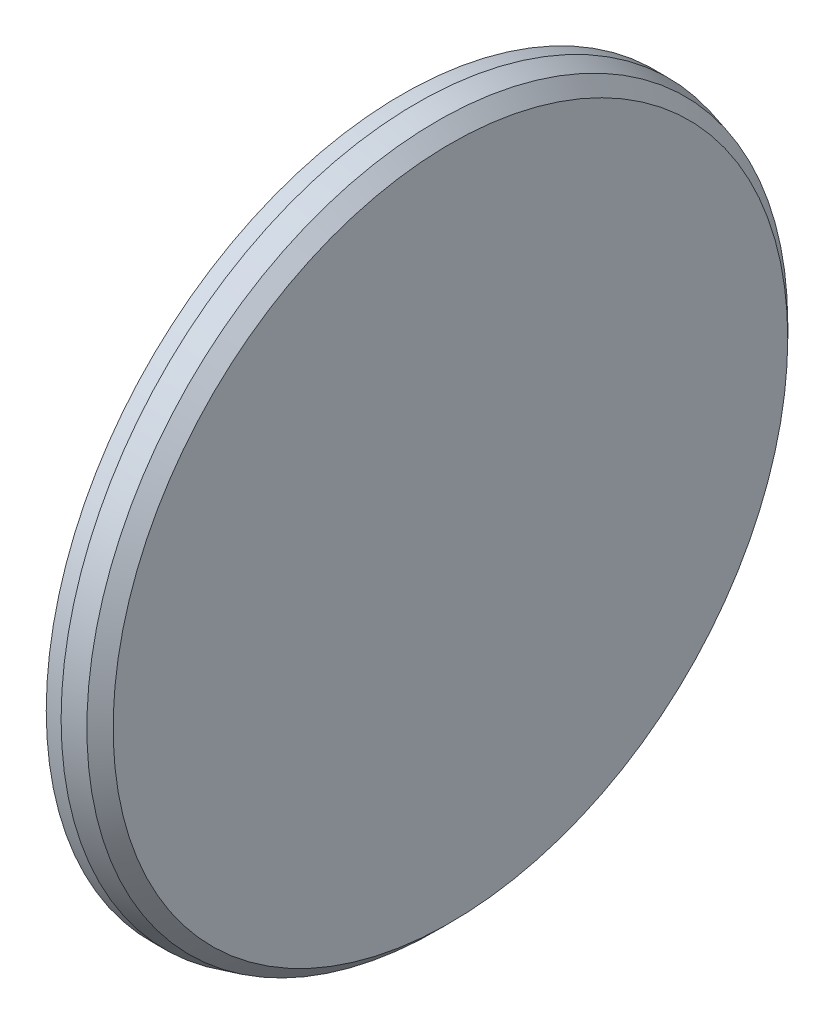
SolidWorks part; units mm, degrees
material "1060 Alloy"
ref_plane "Front Plane" through (0, 0, 0) normal (0, 0, 1) x (1, 0, 0)
ref_plane "Top Plane" through (0, 0, 0) normal (0, 1, 0) x (1, 0, 0)
ref_plane "Right Plane" through (0, 0, 0) normal (1, 0, 0) x (0, 0, -1)
sketch "Sketch1" plane through (0, 0, 0) normal (0, 1, 0) x (1, 0, 0)
  line L0 (0, 0) -> (-85, 0) construction
  line L1 (-85, 0) -> (-85, 100)
  line L2 (-85, 100) -> (-30, 100)
  line L3 (-30, 100) -> (-30, 433.75)
  line L4 (-30, 433.75) -> (-65, 433.75)
  line L5 (-65, 433.75) -> (-65, 478.75)
  line L6 (-65, 478.75) -> (-45, 478.75)
  line L7 (-45, 478.75) -> (-17.6795, 471.4295)
  line L8 (-17.6795, 471.4295) -> (0, 453.75)
  line L9 (0, 453.75) -> (0, 0)
  line L10 (0, 0) -> (-85, 0)
  point P10 (-55, 478.75)
  dimension "D1" = 100
  dimension "D2" = 20
  dimension "D3" = 45
  dimension "D4" = 15
  dimension "D5" = 45
  dimension "D6" = 30
  dimension "D7" = 65
  dimension "D8" = 85
  dimension "D9" = 478.75
  dimension "D10" = 453.75
revolve "Revolve1" add sketch "Sketch1" angle 360 about L0
sketch "Sketch2" plane through (-30, 0, 0) normal (-1, 0, 0) x (0, 0, 1)
  line L0 (0, 100) -> (0, 433.75) construction
  line L1 (20, 105.8301) -> (20, 422.6867)
  line L2 (-20, 105.8301) -> (-20, 365.0877)
  line L3 (-20, 100) -> (-20, 433.75) construction
  line L4 (20, 100) -> (20, 433.75) construction
  line L5 (83.3471, 68.2148) -> (287.0187, 310.9411)
  line L6 (52.7054, 93.9263) -> (219.353, 292.5292)
  line L7 (64.2788, 76.6044) -> (278.8091, 332.2718) construction
  line L8 (107.6952, -1.319) -> (419.7381, 53.7026)
  line L9 (100.7493, 38.0734) -> (356.0683, 83.093)
  line L10 (98.4808, 17.3648) -> (427.1604, 75.3199) construction
  line L11 (81.6515, -70.2355) -> (356.0574, -228.6639)
  line L12 (101.6515, -35.5945) -> (326.1753, -165.2234)
  line L13 (86.6025, -50) -> (375.6385, -216.875) construction
  line L14 (17.4022, -106.2881) -> (125.7735, -404.036)
  line L15 (54.9899, -92.6073) -> (143.6612, -336.2299)
  line L16 (34.202, -93.9693) -> (148.3512, -407.5917) construction
  line L17 (-54.9899, -92.6073) -> (-163.3612, -390.3552)
  line L18 (-17.4022, -106.2881) -> (-106.0735, -349.9107)
  line L19 (-34.202, -93.9693) -> (-148.3512, -407.5917) construction
  line L20 (-101.6515, -35.5945) -> (-376.0574, -194.0229)
  line L21 (-81.6515, -70.2355) -> (-306.1753, -199.8644)
  line L22 (-86.6025, -50) -> (-375.6385, -216.875) construction
  line L23 (-100.7493, 38.0734) -> (-412.7922, 93.0949)
  line L24 (-107.6952, -1.319) -> (-363.0142, 43.7007)
  line L25 (-98.4808, 17.3648) -> (-427.1604, 75.3199) construction
  line L26 (-52.7054, 93.9263) -> (-256.3769, 336.6526)
  line L27 (-83.3471, 68.2148) -> (-249.9948, 266.8177)
  line L28 (-64.2788, 76.6044) -> (-278.8091, 332.2718) construction
  circle A0 centre (0, 0) radius 100 construction
  circle A1 centre (0, 0) radius 433.75 construction
  arc A4 (20, 422.6867) -> (30.708, 432.6616) centre (30, 422.6867) cw
  arc A5 (287.0187, 310.9411) -> (301.6332, 311.6993) centre (294.6791, 304.5132) cw
  arc A6 (-20, 365.0877) -> (-92.8428, 423.6972) centre (-80, 365.0877) ccw
  arc A7 (20, 105.8301) -> (27.2727, 96.2091) centre (30, 105.8301) ccw
  arc A8 (-20, 105.8301) -> (-27.2727, 96.2091) centre (-30, 105.8301) cw
  arc A9 (219.353, 292.5292) -> (201.2256, 384.2491) centre (173.3903, 331.0964) ccw
  arc A10 (83.3471, 68.2148) -> (82.7342, 56.1699) centre (91.0076, 61.7869) ccw
  arc A11 (52.7054, 93.9263) -> (40.9499, 91.231) centre (45.0449, 100.3542) cw
  arc A12 (419.7381, 53.7026) -> (431.4209, 44.8895) centre (421.4746, 43.8545) cw
  arc A13 (356.0683, 83.093) -> (401.1383, 165.0066) centre (345.6494, 142.1814) ccw
  arc A14 (107.6952, -1.319) -> (99.4834, -10.1519) centre (109.4317, -11.167) ccw
  arc A15 (100.7493, 38.0734) -> (90.0116, 43.5649) centre (99.0128, 47.9214) cw
  arc A16 (356.0574, -228.6639) -> (359.342, -242.9247) centre (351.0574, -237.3241) cw
  arc A17 (326.1753, -165.2234) -> (413.3539, -131.4443) centre (356.1753, -113.2618) ccw
  arc A18 (81.6515, -70.2355) -> (69.6832, -71.7234) centre (76.6515, -78.8958) ccw
  arc A19 (101.6515, -35.5945) -> (96.9559, -24.4857) centre (106.6515, -26.9343) cw
  arc A20 (125.7735, -404.036) -> (119.1229, -417.0717) centre (116.3766, -407.4562) cw
  arc A21 (143.6612, -336.2299) -> (232.1567, -366.391) centre (200.0428, -315.7086) ccw
  arc A22 (17.4022, -106.2881) -> (7.2775, -99.7348) centre (8.0052, -109.7083) ccw
  arc A23 (54.9899, -92.6073) -> (58.5334, -81.0792) centre (64.3868, -89.1871) cw
  arc A24 (-163.3612, -390.3552) -> (-176.835, -396.0662) centre (-172.7582, -386.935) cw
  arc A25 (-106.0735, -349.9107) -> (-57.6693, -429.8992) centre (-49.692, -370.4319) ccw
  arc A26 (-54.9899, -92.6073) -> (-58.5334, -81.0792) centre (-64.3868, -89.1871) ccw
  arc A27 (-17.4022, -106.2881) -> (-7.2775, -99.7348) centre (-8.0052, -109.7083) cw
  arc A28 (-376.0574, -194.0229) -> (-390.0499, -189.7369) centre (-381.0574, -185.3626) cw
  arc A29 (-306.1753, -199.8644) -> (-320.5111, -292.2528) centre (-276.1753, -251.8259) ccw
  arc A30 (-101.6515, -35.5945) -> (-96.9559, -24.4857) centre (-106.6515, -26.9343) ccw
  arc A31 (-81.6515, -70.2355) -> (-69.6832, -71.7234) centre (-76.6515, -78.8958) cw
  arc A32 (-412.7922, 93.0949) -> (-420.7561, 105.3723) centre (-411.0557, 102.943) cw
  arc A33 (-363.0142, 43.7007) -> (-433.3822, -17.8581) centre (-373.4331, -15.3878) ccw
  arc A34 (-100.7493, 38.0734) -> (-90.0116, 43.5649) centre (-99.0128, 47.9214) ccw
  arc A35 (-107.6952, -1.319) -> (-99.4834, -10.1519) centre (-109.4317, -11.167) cw
  arc A36 (-256.3769, 336.6526) -> (-254.5859, 351.1767) centre (-248.7165, 343.0804) cw
  arc A37 (-249.9948, 266.8177) -> (-343.469, 264.8926) centre (-295.9574, 228.2504) ccw
  arc A38 (-52.7054, 93.9263) -> (-40.9499, 91.231) centre (-45.0449, 100.3542) ccw
  arc A39 (-83.3471, 68.2148) -> (-82.7342, 56.1699) centre (-91.0076, 61.7869) cw
  arc A40 (82.7342, 56.1699) -> (40.9499, 91.231) centre (0, 0) ccw
  arc A41 (-420.7561, 105.3723) -> (-433.3822, -17.8581) centre (0, 0) ccw
  arc A42 (-254.5859, 351.1767) -> (-343.469, 264.8926) centre (0, 0) ccw
  arc A43 (30.708, 432.6616) -> (-92.8428, 423.6972) centre (0, 0) ccw
  arc A44 (-390.0499, -189.7369) -> (-320.5111, -292.2528) centre (0, 0) ccw
  arc A45 (-176.835, -396.0662) -> (-57.6693, -429.8992) centre (0, 0) ccw
  arc A46 (119.1229, -417.0717) -> (232.1567, -366.391) centre (0, 0) ccw
  arc A47 (359.342, -242.9247) -> (413.3539, -131.4443) centre (0, 0) ccw
  arc A48 (431.4209, 44.8895) -> (401.1383, 165.0066) centre (0, 0) ccw
  arc A49 (301.6332, 311.6993) -> (201.2256, 384.2491) centre (0, 0) ccw
  arc A50 (99.4834, -10.1519) -> (90.0116, 43.5649) centre (0, 0) ccw
  arc A51 (27.2727, 96.2091) -> (-27.2727, 96.2091) centre (0, 0) ccw
  arc A52 (-40.9499, 91.231) -> (-82.7342, 56.1699) centre (0, 0) ccw
  arc A53 (-90.0116, 43.5649) -> (-99.4834, -10.1519) centre (0, 0) ccw
  arc A54 (-96.9559, -24.4857) -> (-69.6832, -71.7234) centre (0, 0) ccw
  arc A55 (-58.5334, -81.0792) -> (-7.2775, -99.7348) centre (0, 0) ccw
  arc A56 (7.2775, -99.7348) -> (58.5334, -81.0792) centre (0, 0) ccw
  arc A57 (69.6832, -71.7234) -> (96.9559, -24.4857) centre (0, 0) ccw
  circle A58 centre (0, 0) radius 433.75 construction
  point P139 (0, 0)
  dimension "D3" = 10
  dimension "D4" = 60
  dimension "D5" = 10
  dimension "D6" = 9
  dimension "D7" = 433.75
  dimension "D8" = 100
  dimension "D1" = 20
  dimension "D2" = 20
extrude "Boss-Extrude1" add sketch "Sketch2" along normal blind 25
